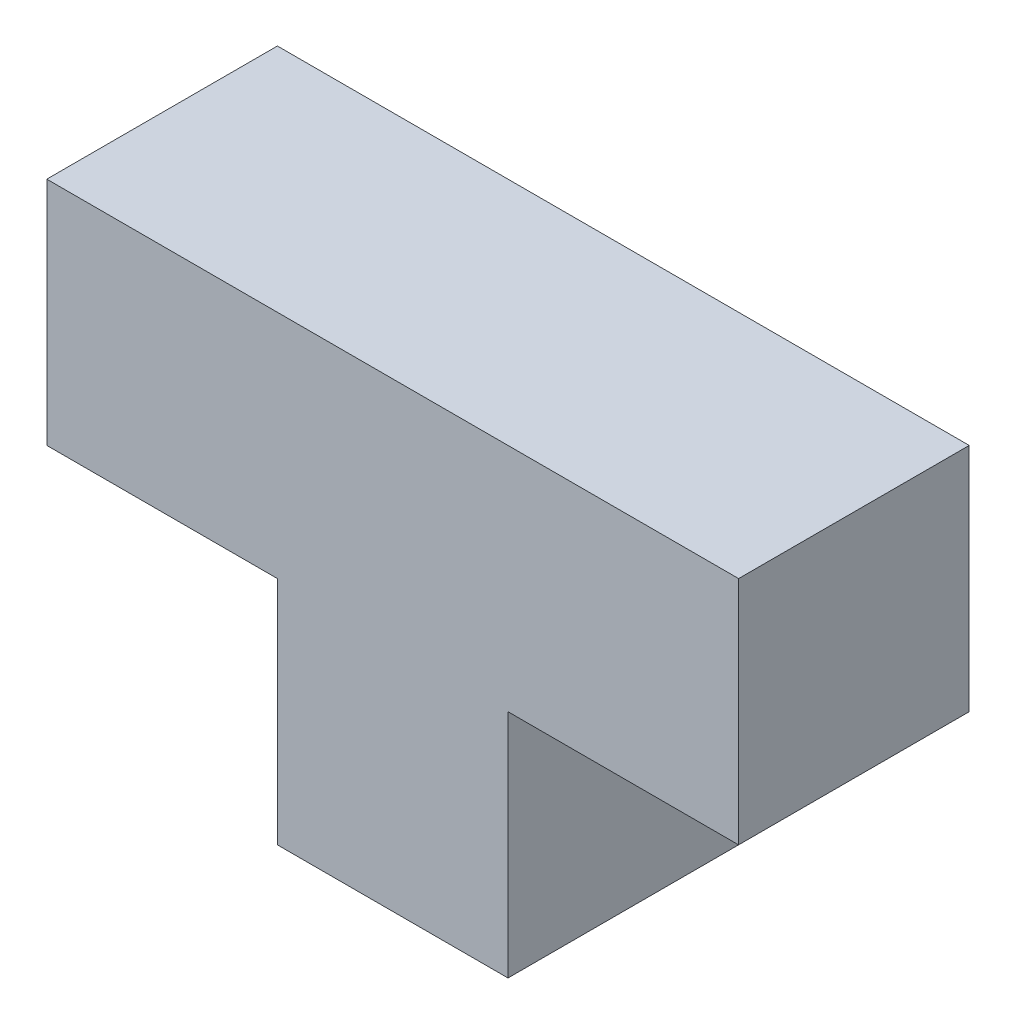
SolidWorks part; units mm, degrees
ref_plane "Front Plane" through (0, 0, 0) normal (0, 0, 1) x (1, 0, 0)
ref_plane "Top Plane" through (0, 0, 0) normal (0, 1, 0) x (1, 0, 0)
ref_plane "Right Plane" through (0, 0, 0) normal (1, 0, 0) x (0, 0, -1)
sketch "Sketch1" plane through (0, 0, 0) normal (0, 0, 1) x (1, 0, 0)
  line L0 (0, 0) -> (0, 19.05)
  line L1 (0, 19.05) -> (-19.05, 19.05)
  line L2 (-19.05, 19.05) -> (-19.05, 38.1)
  line L3 (-19.05, 38.1) -> (38.1, 38.1)
  line L4 (38.1, 38.1) -> (38.1, 19.05)
  line L5 (38.1, 19.05) -> (19.05, 19.05)
  line L6 (19.05, 19.05) -> (19.05, 0)
  line L7 (19.05, 0) -> (0, 0)
  dimension "D1" = 57.15
  dimension "D2" = 19.05
  dimension "D3" = 19.05
  dimension "D4" = 19.05
  dimension "D5" = 19.05
extrude "Boss-Extrude1" add sketch "Sketch1" along normal blind 19.05 contours L7 L0 L1 L2 L3 L4 L5 L6
